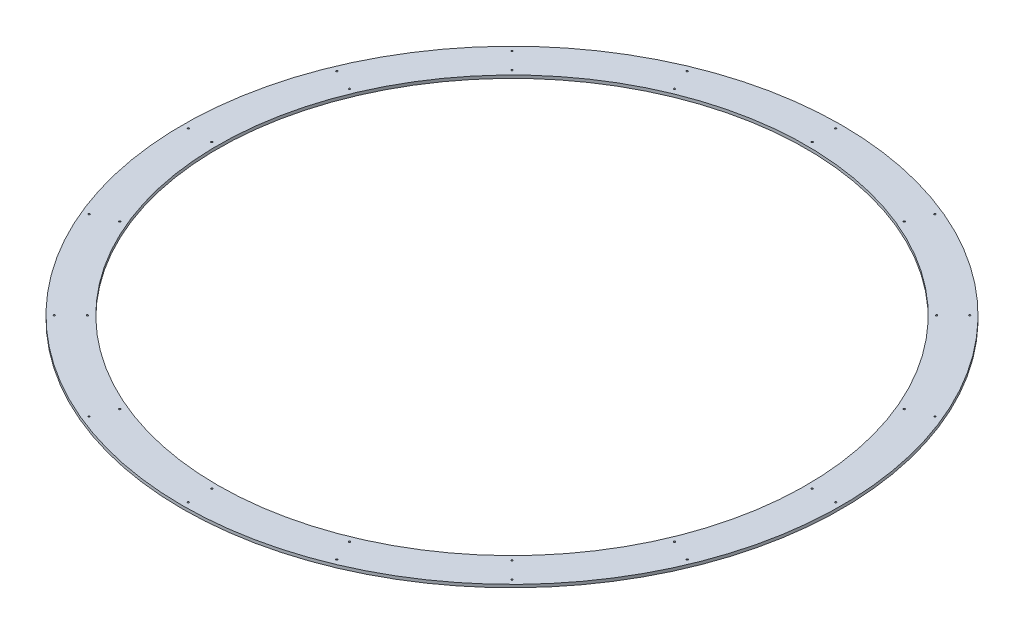
SolidWorks part; units mm, degrees
ref_plane "Front Plane" through (0, 0, 0) normal (0, 0, 1) x (1, 0, 0)
ref_plane "Top Plane" through (0, 0, 0) normal (0, 1, 0) x (1, 0, 0)
ref_plane "Right Plane" through (0, 0, 0) normal (1, 0, 0) x (0, 0, -1)
sketch "Sketch1" plane through (0, 0, 0) normal (0, 1, 0) x (1, 0, 0)
  circle A0 centre (0, 0) radius 636.6198
  circle A1 centre (0, 0) radius 712.8198
  dimension "D1" = 1273.2395
  dimension "D2" = 76.2
extrude "TrackTop" add sketch "Sketch1" along normal blind 6.35
sketch "Sketch6" plane through (0, 0, 0) normal (0, 1, 0) x (1, 0, 0)
  line L0 (636.6198, 0) -> (0, 0) construction
  line L1 (636.6198, 0) -> (649.3198, 0) construction
  line L2 (649.3198, 0) -> (700.1198, 0) construction
  line L3 (700.1198, 0) -> (712.8198, 0) construction
  circle A0 centre (649.3198, 0) radius 1.8288
  circle A1 centre (700.1198, 0) radius 1.8288
  circle A2 centre (0, 0) radius 636.6198 construction
  circle A3 centre (0, 0) radius 712.8198 construction
  dimension "D1" = 3.6576
  dimension "D2" = 12.7
  dimension "D3" = 50.8
sketch "Sketch8" plane through (0, 0, 0) normal (0, 0, 1) x (1, 0, 0)
  line L0 (0, 0) -> (0, 229.6647)
extrude "MountingHoles" cut sketch "Sketch6" along normal through all both and the other way through all
pattern_circular "CirPattern3" count 16 over 360 about axis through (0, 0, 0) along (0, 1, 0) of "MountingHoles"
equation "\"InternalCircumference\"= 4m"
equation "\"D1@Sketch1\"=\"InternalCircumference\"/PI"
equation "\"TrackWidth\"=76.2"
equation "\"D2@Sketch1\"=\"TrackWidth\""
equation "\"WallStudDiameter\"=6.35"
equation "\"D1@Sketch4\"=90"
equation "\"D2@Sketch4\"=360/32"
equation "\"SandwichBoltDiameter\"= 0.1440in'6-32"
equation "\"D1@Sketch6\"=\"SandwichBoltDiameter\""
equation "\"HoleEdgeSpacing\"= 1in / 2"
equation "\"D2@Sketch6\"=\"HoleEdgeSpacing\""
equation "\"TeeNutWidth\"= 6.35'4-40"
equation "\"TeeNutHeight\"= 2.38125'4-40"
equation "\"TeeNutDrillSize\"= 3.048'4-40"
equation "\"HollowWallThickness\"=9.525"
equation "\"LegHoleDiameter\"= 13in / 8'1.25 in PVC"
